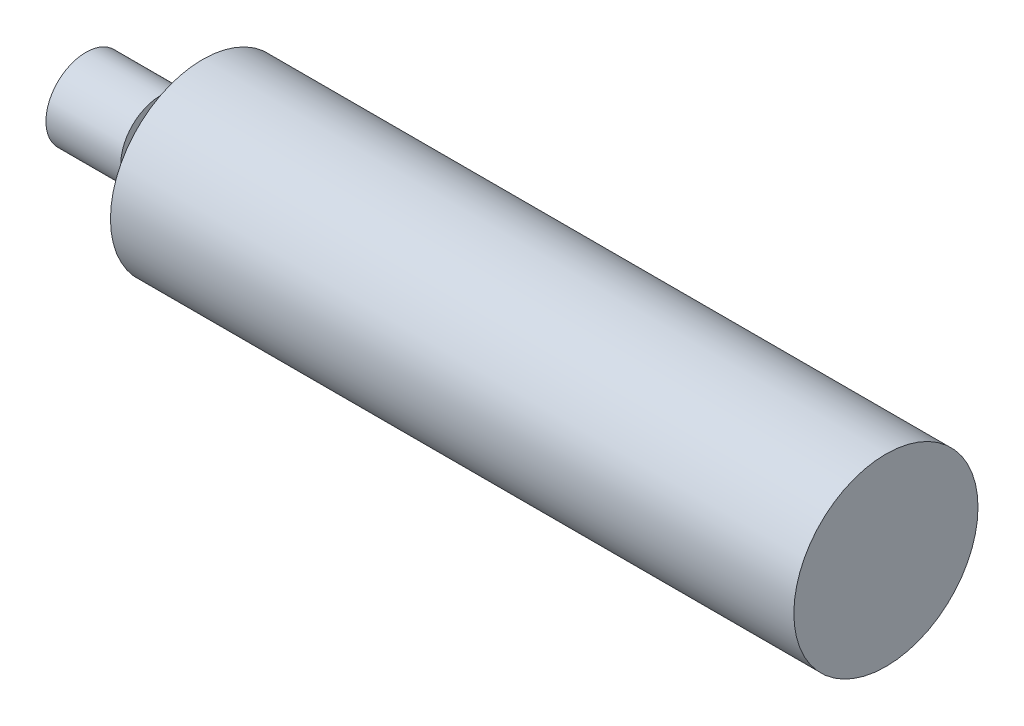
SolidWorks part; units mm, degrees
ref_plane "Front Plane" through (0, 0, 0) normal (0, 0, 1) x (1, 0, 0)
ref_plane "Top Plane" through (0, 0, 0) normal (0, 1, 0) x (1, 0, 0)
ref_plane "Right Plane" through (0, 0, 0) normal (1, 0, 0) x (0, 0, -1)
sketch "Sketch1" plane through (0, 0, 0) normal (0, 1, 0) x (1, 0, 0)
  line L0 (0, 0) -> (0, 4.7625)
  line L1 (0, 4.7625) -> (8.922, 4.7625)
  line L2 (8.922, 4.7625) -> (8.922, 2.9972)
  line L3 (8.922, 2.9972) -> (10.922, 2.9972)
  line L4 (10.922, 2.9972) -> (10.922, 6.0071)
  line L5 (10.922, 6.0071) -> (13.922, 6.0071)
  line L6 (13.922, 6.0071) -> (13.922, 10.9855)
  line L7 (13.922, 10.9855) -> (95.456, 10.9855)
  line L8 (0, 0) -> (95.456, 0)
  line L10 (95.456, 0) -> (95.456, 10.9855)
  line L11 (95.456, 0) -> (0, 0) construction
  point P4 (46.5733, 0)
  point P11 (0, 0)
  point P16 (66.4413, 9.1745)
  dimension "D1" = 9.525
  dimension "D2" = 5.9944
  dimension "D3" = 12.0142
  dimension "D4" = 21.971
  dimension "D5" = 10.922
  dimension "D6" = 81.534
  dimension "D7" = 3
  dimension "D8" = 2
revolve "Revolve1" add sketch "Sketch1" angle 360 about L11
